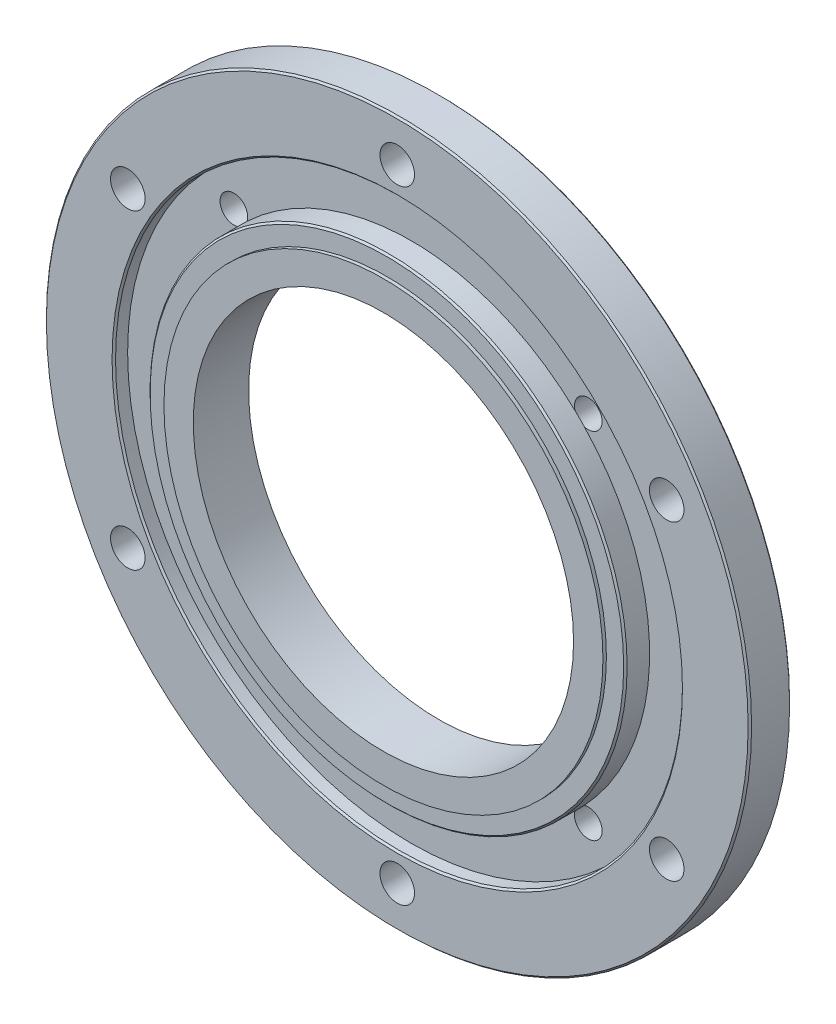
SolidWorks part; units mm, degrees
ref_plane "前视基准面" through (0, 0, 0) normal (0, 0, 1) x (1, 0, 0)
ref_plane "上视基准面" through (0, 0, 0) normal (0, 1, 0) x (1, 0, 0)
ref_plane "右视基准面" through (0, 0, 0) normal (1, 0, 0) x (0, 0, -1)
other "Configuration Table"
sketch "草图1" plane through (0, 0, 0) normal (0, 0, 1) x (1, 0, 0)
  circle A0 centre (0, 0) radius 102
  dimension "D1" = 204
extrude "凸台-拉伸1" add sketch "草图1" along normal blind 12
sketch "草图2" plane through (0, 0, 12) normal (0, 0, 1) x (1, 0, 0)
  circle A0 centre (0, 0) radius 69
  dimension "D1" = 138
extrude "凸台-拉伸2" add sketch "草图2" along normal blind 3
sketch "草图3" plane through (0, 0, 15) normal (0, 0, 1) x (1, 0, 0)
  circle A0 centre (0, 0) radius 63.5
  dimension "D1" = 127
extrude "凸台-拉伸3" add sketch "草图3" along normal blind 1
sketch "草图4" plane through (0, 0, 16) normal (0, 0, 1) x (1, 0, 0)
  circle A0 centre (0, 0) radius 55
  dimension "D1" = 110
extrude "切除-拉伸1" cut sketch "草图4" against normal through all
sketch "草图5" plane through (0, 0, 16) normal (0, 0, 1) x (1, 0, 0)
  circle A0 centre (0, 0) radius 82
  circle A1 centre (0, 0) radius 69 construction
  circle A2 centre (0, 0) radius 69
  dimension "D1" = 164
extrude "切除-拉伸2" cut sketch "草图5" against normal blind 4 from surface at -4 starting at face at (69, 0, 12)
sketch "草图6" plane through (0, 0, 0) normal (0, 0, 1) x (1, 0, 0)
  line L0 (0, 0) -> (0, 102) construction
  line L1 (0, 0) -> (55, 0) construction
  circle A0 centre (0, 0) radius 72.5 construction
  circle A1 centre (-51.2652, 51.2652) radius 4
  circle A2 centre (0, 0) radius 102 construction
  circle A3 centre (51.2652, 51.2652) radius 4
  circle A4 centre (0, 0) radius 55 construction
  circle A5 centre (51.2652, -51.2652) radius 4
  circle A6 centre (-51.2652, -51.2652) radius 4
  dimension "D1" = 145
  dimension "D2" = 8
  dimension "D3" = 90
extrude "切除-拉伸3" cut sketch "草图6" along normal blind 8
sketch "草图7" plane through (0, 0, 0) normal (0, 0, -1) x (-1, 0, 0)
  line L0 (0, 0) -> (0, 90) construction
  line L1 (0, 0) -> (-55, 0) construction
  circle A0 centre (0, 0) radius 90 construction
  circle A1 centre (-77.9423, 45) radius 5
  circle A2 centre (0, 0) radius 55 construction
  circle A6 centre (0, 90) radius 5
  circle A7 centre (77.9423, 45) radius 5
  circle A8 centre (77.9423, -45) radius 5
  circle A9 centre (0, -90) radius 5
  circle A10 centre (-77.9423, -45) radius 5
  point P22 (0, 0)
  dimension "D1" = 180
  dimension "D2" = 10
  dimension "D3" = 60
  dimension "D4" = 6
extrude "切除-拉伸4" cut sketch "草图7" against normal through all
chamfer "倒角1" distance 0.5 angle 45 4 edges at (82, 0, 12) (69, 0, 15) (102, 0, 12) (102, 0, 0)
